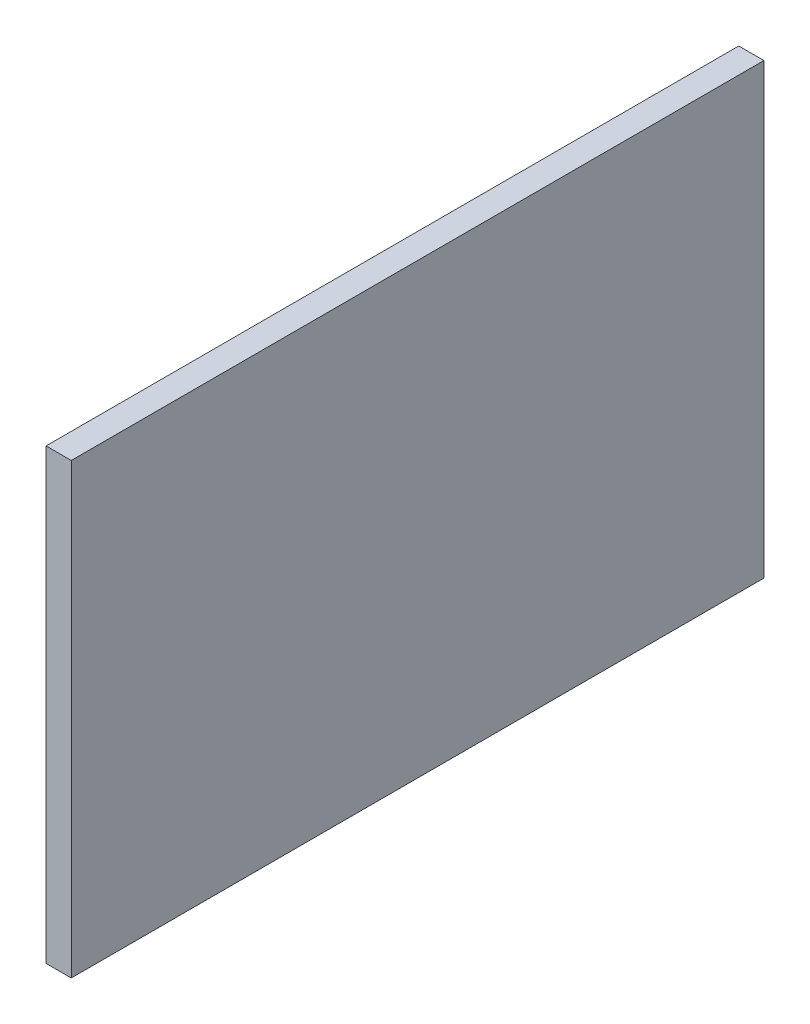
SolidWorks part; units mm, degrees
ref_plane "Ön Düzlem" through (0, 0, 0) normal (0, 0, 1) x (1, 0, 0)
ref_plane "Üst Düzlem" through (0, 0, 0) normal (0, 1, 0) x (1, 0, 0)
ref_plane "Sağ Düzlem" through (0, 0, 0) normal (1, 0, 0) x (0, 0, -1)
sketch "Çizim1" plane through (0, 0, 0) normal (1, 0, 0) x (0, 0, -1)
  line L0 (0, 0) -> (0, 177.95)
  line L1 (0, 177.95) -> (275, 177.95)
  line L2 (275, 177.95) -> (275, 0)
  line L3 (275, 0) -> (0, 0)
  dimension "D1" = 177.95
  dimension "D2" = 275
extrude "Yükseklik-Ekstrüzyon1" add sketch "Çizim1" along normal blind 10
